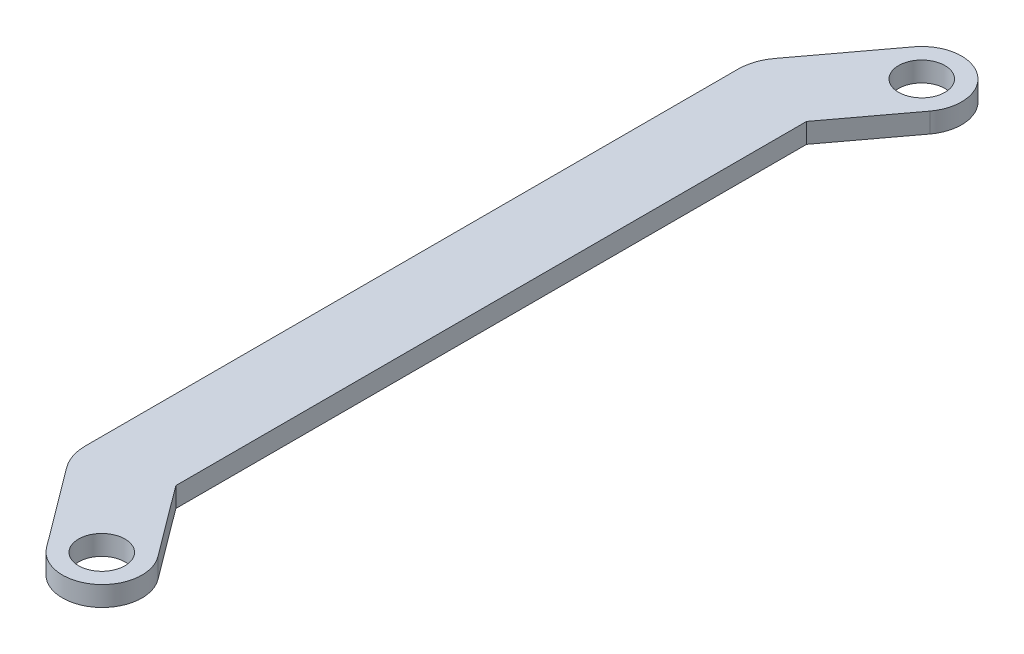
SolidWorks part; units mm, degrees
ref_plane "Front Plane" through (0, 0, 0) normal (0, 0, 1) x (1, 0, 0)
ref_plane "Top Plane" through (0, 0, 0) normal (0, 1, 0) x (1, 0, 0)
ref_plane "Right Plane" through (0, 0, 0) normal (1, 0, 0) x (0, 0, -1)
sketch "Sketch1" plane through (0, 0, 0) normal (0, 1, 0) x (1, 0, 0)
  line L0 (-13.3181, 0) -> (17.0874, 0) construction
  line L1 (-4.8087, 65.3984) -> (-13.7505, 53.416)
  line L2 (-15.1404, 49.2295) -> (-15.1404, 0)
  line L3 (4.8087, 58.2216) -> (-3.1404, 47.5695)
  line L4 (-3.1404, 47.5695) -> (-3.1404, 0)
  line L5 (-3.1404, -47.5695) -> (-3.1404, 0)
  line L6 (4.8087, -58.2216) -> (-3.1404, -47.5695)
  line L7 (-4.8087, -65.3984) -> (-13.7505, -53.416)
  line L8 (-15.1404, -49.2295) -> (-15.1404, 0)
  circle A0 centre (0, 61.81) radius 3.5
  circle A1 centre (0, -61.881) radius 3.5
  arc A2 (4.8087, 58.2216) -> (-4.8087, 65.3984) centre (0, 61.81) ccw
  arc A4 (-15.1404, 49.2295) -> (-13.7505, 53.416) centre (-8.1404, 49.2295) cw
  arc A5 (-3.1404, 47.5695) -> (-3.1404, 47.5695) centre (-3.1404, 47.5695) cw
  arc A6 (-15.1404, -49.2295) -> (-13.7505, -53.416) centre (-8.1404, -49.2295) ccw
  arc A7 (4.8087, -58.2216) -> (-4.8087, -65.3984) centre (0, -61.81) cw
  dimension "D1" = 7
  dimension "D2" = 7
  dimension "D3" = 6
  dimension "D7" = 7
  dimension "D5" = 61.81
  dimension "D6" = 61.881
  dimension "D8" = 12
extrude "Boss-Extrude1" add sketch "Sketch1" along normal blind 3
